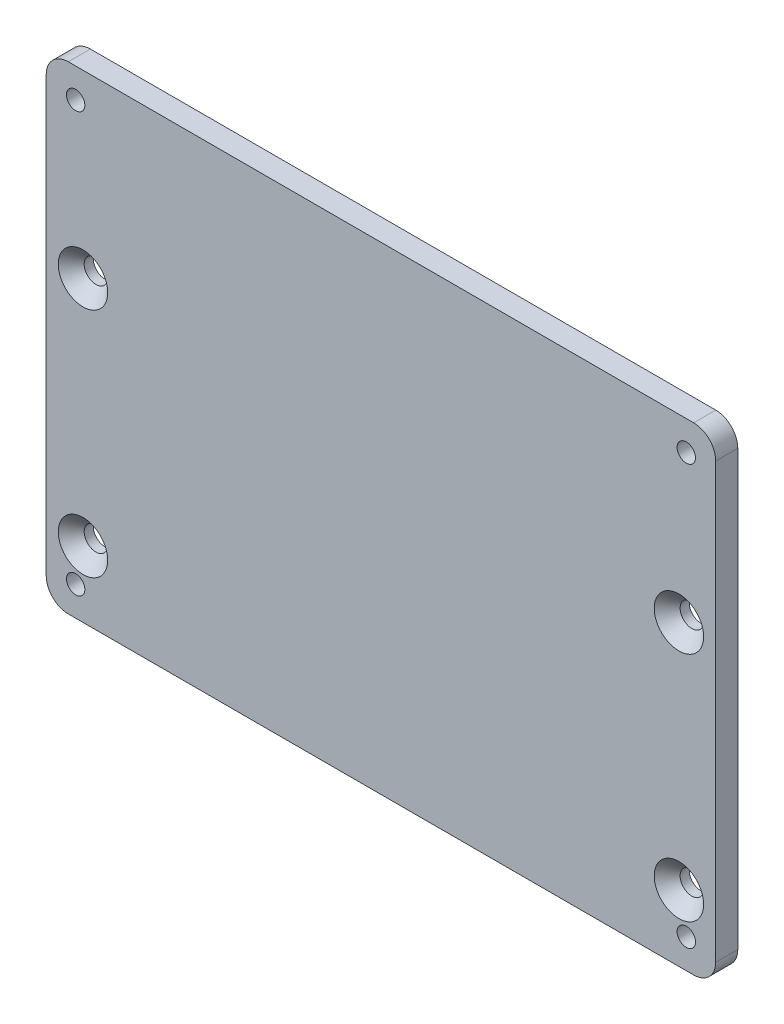
SolidWorks part; units mm, degrees
material "6061-T6 (SS)"
ref_plane "Front Plane" through (0, 0, 0) normal (0, 0, 1) x (1, 0, 0)
ref_plane "Top Plane" through (0, 0, 0) normal (0, 1, 0) x (1, 0, 0)
ref_plane "Right Plane" through (0, 0, 0) normal (1, 0, 0) x (0, 0, -1)
sketch "Sketch1" plane through (0, 0, 0) normal (0, 0, 1) x (1, 0, 0)
  line L1 (45.5, -32.5) -> (-45.5, -32.5)
  line L2 (45.5, -32.5) -> (45.5, 32.5)
  line L3 (45.5, 32.5) -> (-45.5, 32.5)
  line L4 (-45.5, -32.5) -> (-45.5, 32.5)
  line L5 (45.5, -32.5) -> (-45.5, 32.5) construction
  line L6 (45.5, 32.5) -> (-45.5, -32.5) construction
  point P0 (0, 0)
  dimension "D1" = 91
  dimension "D2" = 65
extrude "Boss-Extrude1" add sketch "Sketch1" along normal blind 3
sketch "Sketch2" plane through (0, 0, 3) normal (0, 0, 1) x (1, 0, 0)
  line L1 (41.5, -28.5) -> (-41.5, -28.5)
  line L2 (41.5, -28.5) -> (41.5, 28.5)
  line L3 (41.5, 28.5) -> (-41.5, 28.5)
  line L4 (-41.5, -28.5) -> (-41.5, 28.5)
  line L5 (41.5, -28.5) -> (-41.5, 28.5) construction
  line L6 (41.5, 28.5) -> (-41.5, -28.5) construction
  point P0 (0, 0)
  dimension "D1" = 57
  dimension "D2" = 83
hole_wizard "Tap Drill for M3x0.5 Tap1" positions "Sketch3" profile "Sketch4" hole size "M3x0.5" standard "ANSI Metric" end condition through all
sketch "Sketch3" plane through (0, 0, 3) normal (0, 0, 1) x (1, 0, 0)
  point P0 (-41.5, 28.5)
  point P3 (41.5, 28.5)
  point P6 (41.5, -28.5)
  point P9 (-41.5, -28.5)
sketch "Sketch4" plane through (-41.5, 28.5, 3) normal (1, 0, 0) x (0, -1, 0)
  line L0 (0, 0) -> (0, 3)
  line L1 (0, 3) -> (1.25, 3)
  line L2 (1.25, 3) -> (1.25, 0)
  line L5 (1.25, 0) -> (0, 0)
  line L11 (0, -6.35) -> (0, 107.95) construction
  dimension "Thru Hole Dia." = 2.5
  dimension "Thru Hole Depth" = 3
fillet "Fillet1" radius 3 4 edges at (45.5, 32.5, 1.5) (45.5, -32.5, 1.5) (-45.5, -32.5, 1.5) (-45.5, 32.5, 1.5)
sketch "Sketch5" plane through (0, 0, 3) normal (0, 0, 1) x (1, 0, 0)
  line L0 (-45.5, 29.5) -> (-45.5, -29.5) construction
  line L1 (40.5, -23.5) -> (-40.5, -23.5)
  line L2 (40.5, -23.5) -> (40.5, 8)
  line L3 (40.5, 8) -> (-40.5, 8)
  line L4 (-40.5, -23.5) -> (-40.5, 8)
  line L5 (40.5, -23.5) -> (-40.5, 8) construction
  line L6 (40.5, 8) -> (-40.5, -23.5) construction
  point P0 (0, -7.75)
  point P8 (0, 0)
  dimension "D1" = 8
  dimension "5" = 5
  dimension "D2" = 31.5
hole_wizard "CSK for M3 SFHCS1" positions "Sketch6" profile "Sketch7" countersink size "M3" standard "ANSI Metric" end condition through all
sketch "Sketch6" plane through (0, 0, 3) normal (0, 0, 1) x (1, 0, 0)
  point P0 (-40.5, 8)
  point P3 (-40.5, -23.5)
  point P6 (40.5, -23.5)
  point P9 (40.5, 8)
sketch "Sketch7" plane through (-40.5, 8, 3) normal (1, 0, 0) x (0, -1, 0)
  line L0 (0, 0) -> (0, 3)
  line L1 (0, 3) -> (1.6, 3)
  line L2 (1.6, 3) -> (1.6, 1.76)
  line L3 (1.6, 1.76) -> (3.36, 0)
  line L5 (3.36, 0) -> (0, 0)
  line L6 (-1.6, 1.76) -> (-3.36, 0) construction
  line L11 (0, -6.35) -> (0, 107.95) construction
  dimension "Thru Hole Dia." = 3.2
  dimension "Thru Hole Depth" = 3
  dimension "Near C'Sink Dia." = 6.72
  dimension "Near C'Sink Angle" = 90
